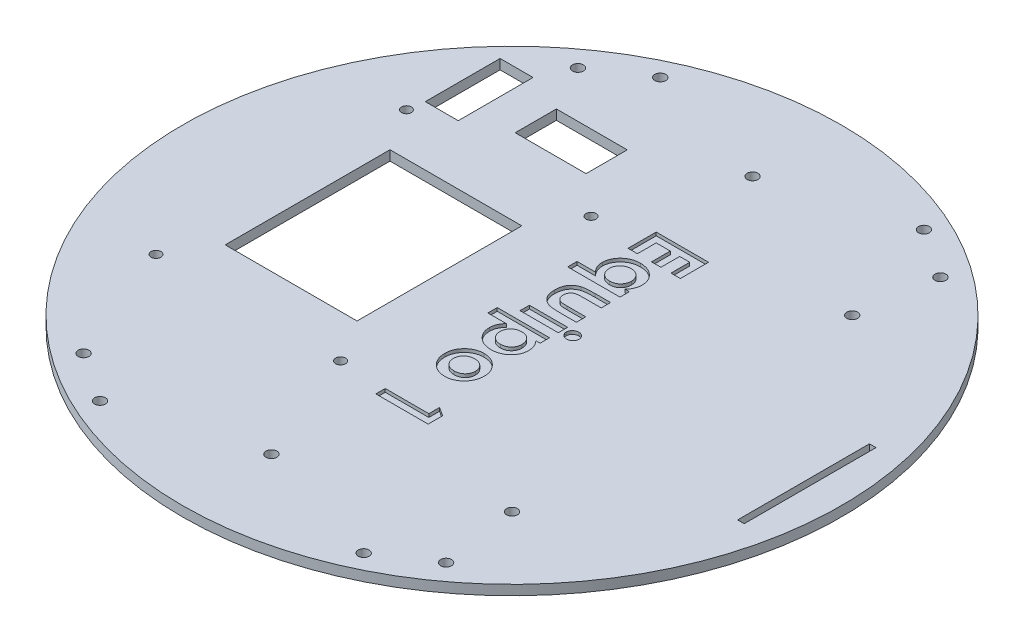
SolidWorks part; units mm, degrees
ref_plane "Alzado" through (0, 0, 0) normal (0, 0, 1) x (1, 0, 0)
ref_plane "Planta" through (0, 0, 0) normal (0, 1, 0) x (1, 0, 0)
ref_plane "Vista lateral" through (0, 0, 0) normal (1, 0, 0) x (0, 0, -1)
sketch "Croquis1" plane through (0, 0, 0) normal (0, 1, 0) x (1, 0, 0)
  line L0 (0, 71.35) -> (0, -71.35) construction
  line L5 (0, 0) -> (54.5026, 0) construction
  line L12 (-69.2993, 65.6851) -> (-59.2993, 65.6851)
  line L13 (-69.2993, 65.6851) -> (-69.2993, 42.9851)
  line L14 (-69.2993, 42.9851) -> (-59.2993, 42.9851)
  line L15 (-59.2993, 65.6851) -> (-59.2993, 42.9851)
  line L17 (-72.0203, 40) -> (-12.0203, 40) construction
  line L18 (-72.0203, 40) -> (-72.0203, -40) construction
  line L19 (-72.0203, -40) -> (-12.0203, -40) construction
  line L20 (-12.0203, 40) -> (-12.0203, -40) construction
  line L22 (-47.4922, 60.9632) -> (-25.9922, 60.9632)
  line L23 (-47.4922, 60.9632) -> (-47.4922, 48.4632)
  line L24 (-47.4922, 48.4632) -> (-25.9922, 48.4632)
  line L25 (-25.9922, 60.9632) -> (-25.9922, 48.4632)
  line L27 (-7, -66) -> (7, -66) construction
  line L28 (-7, -66) -> (-7, -97) construction
  line L29 (-7, -97) -> (7, -97) construction
  line L30 (7, -66) -> (7, -97) construction
  line L31 (41.7193, -51.6188) -> (51.6188, -41.7193) construction
  line L32 (41.7193, -51.6188) -> (63.6396, -73.5391) construction
  line L33 (63.6396, -73.5391) -> (73.5391, -63.6396) construction
  line L34 (51.6188, -41.7193) -> (73.5391, -63.6396) construction
  line L35 (66, -7) -> (66, 7) construction
  line L36 (66, -7) -> (97, -7) construction
  line L37 (97, -7) -> (97, 7) construction
  line L38 (66, 7) -> (97, 7) construction
  line L39 (51.6188, 41.7193) -> (41.7193, 51.6188) construction
  line L40 (51.6188, 41.7193) -> (73.5391, 63.6396) construction
  line L41 (73.5391, 63.6396) -> (63.6396, 73.5391) construction
  line L42 (41.7193, 51.6188) -> (63.6396, 73.5391) construction
  line L43 (7, 66) -> (-7, 66) construction
  line L44 (7, 66) -> (7, 97) construction
  line L45 (7, 97) -> (-7, 97) construction
  line L46 (-7, 66) -> (-7, 97) construction
  line L47 (0, 0) -> (-45.7335, 0) construction
  line L49 (-62.0203, 25) -> (-22.0203, 25)
  line L50 (-62.0203, 25) -> (-62.0203, -25)
  line L51 (-62.0203, -25) -> (-22.0203, -25)
  line L52 (-22.0203, 25) -> (-22.0203, -25)
  line L53 (88, 20.4593) -> (90, 20.4593)
  line L54 (88, 20.4593) -> (88, -19.5407)
  line L55 (88, -19.5407) -> (90, -19.5407)
  line L56 (90, 20.4593) -> (90, -19.5407)
  circle A6 centre (55, 75) radius 1.65
  circle A8 centre (55, -75) radius 1.65
  circle A10 centre (0, -73) radius 1.65
  circle A11 centre (51.6188, -51.6188) radius 1.65
  circle A13 centre (51.6188, 51.6188) radius 1.65
  circle A14 centre (0, 73) radius 1.65
  circle A15 centre (40, -85) radius 1.65
  circle A16 centre (40, 85) radius 1.65
  circle A19 centre (0, 0) radius 100
  circle A20 centre (73, 0) radius 1.65 [skipped]
  circle A21 centre (-70.0203, 38) radius 1.5
  circle A22 centre (-14.0203, 38) radius 1.5
  circle A23 centre (-14.0203, -38) radius 1.5
  circle A24 centre (-70.0203, -38) radius 1.5
  circle A25 centre (-40, -85) radius 1.65
  circle A26 centre (-55, -75) radius 1.65
  circle A27 centre (-55, 75) radius 1.65
  circle A28 centre (-40, 85) radius 1.65
  point P17 (0, 0)
  point P72 (0, 0)
  dimension "D10" = 200
  dimension "D14" = 3.3
  dimension "D3" = 3.3
  dimension "D7" = 3.3
  dimension "D27" = 3
  dimension "D28" = 3
  dimension "D2" = 73
  dimension "D4" = 5
  dimension "D5" = 75
  dimension "D6" = 55
  dimension "D8" = 40
  dimension "D9" = 85
  dimension "D15" = 22.7
  dimension "D16" = 10
  dimension "D17" = 80
  dimension "D18" = 60
  dimension "D19" = 40
  dimension "D20" = 21.5
  dimension "D21" = 12.5
  dimension "D22" = 14
  dimension "D23" = 7
  dimension "D24" = 31
  dimension "D25" = 7
  dimension "D29" = 2
  dimension "D30" = 2
  dimension "D31" = 2
  dimension "D32" = 2
  dimension "D33" = 50
  dimension "D34" = 40
  dimension "D35" = 10
  dimension "D36" = 40
  dimension "D37" = 2
  dimension "D38" = 90
  dimension "D26" = 5
extrude "Saliente-Extruir1" add sketch "Croquis1" along normal blind 3
sketch "Croquis2" plane through (0, 3, 0) normal (0, 1, 0) x (1, 0, 0)
  line L0 (0, 50) -> (0, -50) construction
  text T0 "Equipo 1" font "Century Gothic" height in points 60
  dimension "D1" = 100
  dimension "D2" = 50
extrude "Cortar-Extruir1" cut sketch "Croquis2" against normal blind 1
